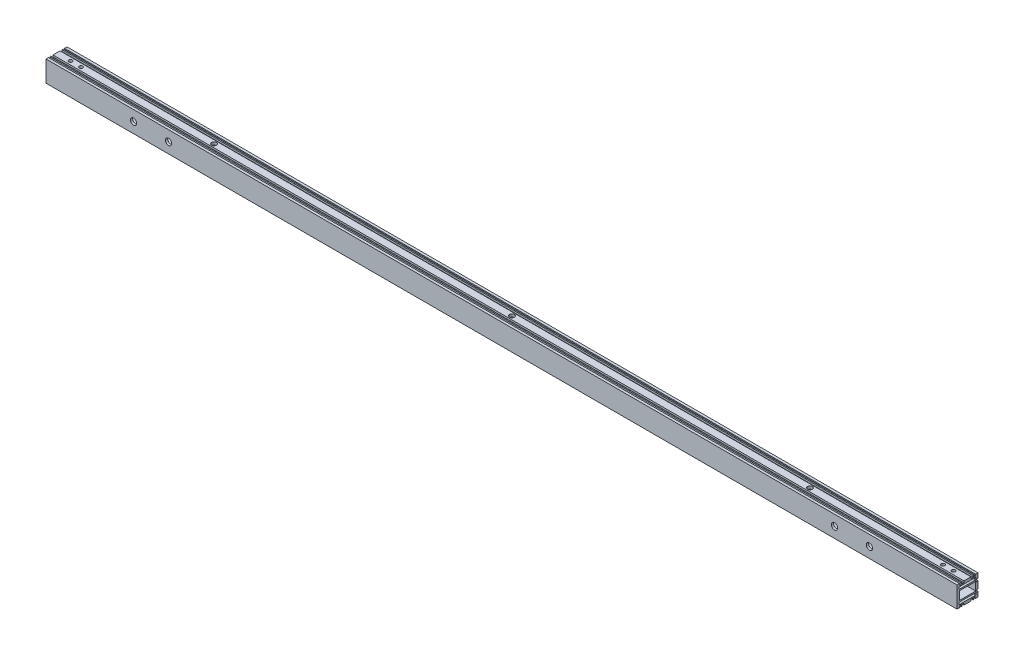
SolidWorks part; units mm, degrees
ref_plane "前视基准面" through (0, 0, 0) normal (0, 0, 1) x (1, 0, 0)
ref_plane "上视基准面" through (0, 0, 0) normal (0, 1, 0) x (1, 0, 0)
ref_plane "右视基准面" through (0, 0, 0) normal (1, 0, 0) x (0, 0, -1)
sketch "草图1" plane through (0, 0, 0) normal (1, 0, 0) x (0, 0, -1)
  line L0 (-15, 15) -> (15, -15) construction
  line L1 (-15, 15) -> (-11.5, 15)
  line L2 (-15, 15) -> (-15, -15)
  line L3 (-15, -15) -> (-11.5, -15)
  line L4 (15, 15) -> (15, 8)
  line L5 (15, 15) -> (-15, -15) construction
  line L6 (-11.5, 15) -> (-11.5, 13.5)
  line L7 (-11.5, 13.5) -> (-11, 13.5)
  line L8 (-11, 13.5) -> (-11, 12)
  line L9 (-11, 12) -> (-9.5, 12)
  line L10 (-9.5, 12) -> (-9.5, 15)
  line L11 (-9.5, 15) -> (-8, 15)
  line L12 (-8, 15) -> (-8, 12.5)
  line L13 (-8, 12.5) -> (-5, 12.5)
  line L14 (-5, 12.5) -> (-5, 15)
  line L15 (-5, 15) -> (5, 15)
  line L16 (0, 21.5201) -> (0, -18.309) construction
  line L17 (0, 55) -> (0, -55) construction
  line L18 (5, 12.5) -> (5, 15)
  line L19 (8, 12.5) -> (5, 12.5)
  line L20 (8, 15) -> (8, 12.5)
  line L21 (9.5, 15) -> (8, 15)
  line L22 (9.5, 12) -> (9.5, 15)
  line L23 (11, 12) -> (9.5, 12)
  line L24 (11, 13.5) -> (11, 12)
  line L25 (11.5, 13.5) -> (11, 13.5)
  line L26 (11.5, 15) -> (11.5, 13.5)
  line L27 (8, 15) -> (9.5, 15)
  line L28 (11.5, 15) -> (15, 15)
  line L29 (-19.8303, 0) -> (22.13, 0) construction
  line L30 (55, 0) -> (-55, 0) construction
  line L31 (8, -15) -> (9.5, -15)
  line L32 (11.5, -15) -> (11.5, -13.5)
  line L33 (11.5, -13.5) -> (11, -13.5)
  line L34 (11, -13.5) -> (11, -12)
  line L35 (11, -12) -> (9.5, -12)
  line L36 (9.5, -12) -> (9.5, -15)
  line L37 (9.5, -15) -> (8, -15)
  line L38 (8, -15) -> (8, -12.5)
  line L39 (8, -12.5) -> (5, -12.5)
  line L40 (5, -12.5) -> (5, -15)
  line L41 (-5, -15) -> (5, -15)
  line L42 (-5, -12.5) -> (-5, -15)
  line L43 (-8, -12.5) -> (-5, -12.5)
  line L44 (-8, -15) -> (-8, -12.5)
  line L45 (-9.5, -15) -> (-8, -15)
  line L46 (-9.5, -12) -> (-9.5, -15)
  line L47 (-11, -12) -> (-9.5, -12)
  line L48 (-11, -13.5) -> (-11, -12)
  line L49 (-11.5, -13.5) -> (-11, -13.5)
  line L50 (-11.5, -15) -> (-11.5, -13.5)
  line L51 (-9.5, -15) -> (-8, -15)
  line L52 (-5, -15) -> (5, -15)
  line L53 (8, -15) -> (9.5, -15)
  line L54 (11.5, -15) -> (15, -15)
  line L55 (15, 8) -> (12.5, 8)
  line L56 (12.5, 8) -> (12.5, 5)
  line L57 (12.5, 5) -> (15, 5)
  line L58 (12.5, -5) -> (15, -5)
  line L59 (12.5, -8) -> (12.5, -5)
  line L60 (15, -8) -> (12.5, -8)
  line L61 (15, 5) -> (15, -5)
  line L62 (15, -8) -> (15, -15)
  line L63 (12, -10.5) -> (12, -8.5)
  line L64 (-11.5, 11) -> (11.5, 11)
  line L65 (-12, 10.5) -> (-12, 8.5)
  line L66 (-11.5, 8) -> (11.5, 8)
  line L67 (12, 10.5) -> (12, 8.5)
  line L68 (-11.5, -8) -> (11.5, -8)
  line L69 (-12, -10.5) -> (-12, -8.5)
  line L70 (-11.5, -11) -> (11.5, -11)
  line L72 (-11.75, 6) -> (11.75, 6)
  line L73 (-11.75, 6) -> (-11.75, -6)
  line L74 (-11.75, -6) -> (11.75, -6)
  line L75 (11.75, 6) -> (11.75, -6)
  arc A0 (12, 8.5) -> (11.5, 8) centre (11.5, 8.5) cw
  arc A1 (11.5, 11) -> (12, 10.5) centre (11.5, 10.5) cw
  arc A2 (-11.5, 11) -> (-12, 10.5) centre (-11.5, 10.5) ccw
  arc A3 (-11.5, 8) -> (-12, 8.5) centre (-11.5, 8.5) cw
  arc A8 (-11.5, -8) -> (-12, -8.5) centre (-11.5, -8.5) ccw
  arc A9 (-11.5, -11) -> (-12, -10.5) centre (-11.5, -10.5) cw
  arc A10 (11.5, -11) -> (12, -10.5) centre (11.5, -10.5) ccw
  arc A11 (12, -8.5) -> (11.5, -8) centre (11.5, -8.5) ccw
  point P69 (12, 11)
  point P72 (-12, 11)
  point P77 (-11, -13.5)
  point P80 (11, -13.5)
  point P83 (11, 13.5)
  point P86 (-11, 13.5)
  point P99 (-12, -11)
  point P100 (12, -11)
  dimension "D17" = 0.5
  dimension "D1" = 3.5
  dimension "D2" = 1.5
  dimension "D3" = 0.5
  dimension "D4" = 1.5
  dimension "D5" = 3
  dimension "D6" = 30
  dimension "D7" = 30
  dimension "D8" = 1.5
  dimension "D9" = 2.5
  dimension "D10" = 3
  dimension "D11" = 2.5
  dimension "D12" = 7
  dimension "D13" = 3
  dimension "D14" = 4
  dimension "D15" = 3
  dimension "D16" = 24
  dimension "D19" = 23.5
  dimension "D20" = 12
extrude "凸台-拉伸1" add sketch "草图1" along normal mid plane 1301
hole_wizard "M6 螺纹孔1" positions "草图3" profile "草图2" tap size "M6" standard "GB"
sketch "草图3" plane through (0, 15, 0) normal (0, 1, 0) x (1, 0, 0)
  point P0 (630.5, 0)
  point P3 (615.5, 0)
  point P6 (-630.5, 0)
  point P9 (-615.5, 0)
sketch "草图2" plane through (630.5, 15, 0) normal (1, 0, 0) x (0, 0, 1)
  line L0 (0, 0) -> (0, 20.5022)
  line L1 (0, 20.5022) -> (2.5, 19)
  line L2 (2.5, 19) -> (2.5, 0)
  line L5 (2.5, 0) -> (0, 0)
  line L10 (0, 20.5022) -> (-2.5, 19) construction
  line L11 (0, -6.35) -> (0, 107.95) construction
  dimension "螺纹孔钻头直径" = 5
  dimension "螺纹孔钻头深度" = 19
  dimension "导头角度" = 118
cosmetic thread "孔螺蚊线1" parameters "D1"=9, "D2"=6
cosmetic thread "孔螺蚊线2" parameters "D1"=9, "D2"=6
cosmetic thread "孔螺蚊线3" parameters "D1"=9, "D2"=6
cosmetic thread "孔螺蚊线4" parameters "D1"=9, "D2"=6
hole_wizard "M6 螺纹孔2" positions "草图5" profile "草图4" tap size "M6" standard "GB"
sketch "草图5" plane through (0, 0, -15) normal (0, 0, -1) x (-1, 0, 0)
  point P0 (-630.5, 0)
  point P3 (-615.5, 0)
  point P6 (615.5, 0)
  point P9 (630.5, 0)
sketch "草图4" plane through (630.5, 0, -15) normal (1, 0, 0) x (0, 1, 0)
  line L0 (0, 0) -> (0, 20.5022)
  line L1 (0, 20.5022) -> (2.5, 19)
  line L2 (2.5, 19) -> (2.5, 0)
  line L5 (2.5, 0) -> (0, 0)
  line L10 (0, 20.5022) -> (-2.5, 19) construction
  line L11 (0, -6.35) -> (0, 107.95) construction
  dimension "螺纹孔钻头直径" = 5
  dimension "螺纹孔钻头深度" = 19
  dimension "导头角度" = 118
cosmetic thread "孔螺蚊线5" parameters "D1"=3.25, "D2"=6
cosmetic thread "孔螺蚊线6" parameters "D1"=3.25, "D2"=6
cosmetic thread "孔螺蚊线7" parameters "D1"=3.25, "D2"=6
cosmetic thread "孔螺蚊线8" parameters "D1"=3.25, "D2"=6
hole_wizard "Ø9.0 (9) 直径孔1" positions "草图7" profile "草图8" hole size "Ø9.0" standard "GB" end condition through all
sketch "草图7" plane through (0, 0, 15) normal (0, 0, 1) x (1, 0, 0)
  line L0 (650.5, -15) -> (-650.5, -15) construction
  line L1 (650.5, 15) -> (650.5, -15) construction
  line L2 (650.5, -15) -> (-650.5, -15) construction
  line L3 (-650.5, 15) -> (-650.5, -15) construction
  point P0 (-525.5, 0)
  point P2 (-475.5, 0)
  point P4 (525.5, 0)
  point P6 (475.5, 0)
  dimension "D1" = 15
  dimension "D2" = 125
  dimension "D3" = 15
  dimension "D4" = 175
  dimension "D5" = 15
  dimension "D6" = 125
  dimension "D7" = 15
  dimension "D8" = 175
sketch "草图8" plane through (-525.5, 0, 15) normal (1, 0, 0) x (0, -1, 0)
  line L0 (0, 0) -> (0, 30)
  line L1 (0, 30) -> (4.5, 30)
  line L2 (4.5, 30) -> (4.5, 0)
  line L5 (4.5, 0) -> (0, 0)
  line L11 (0, -6.35) -> (0, 107.95) construction
  dimension "通孔孔直径" = 9
  dimension "通孔孔深度" = 30
hole_wizard "M6 螺纹孔3" positions "草图10" profile "草图11" tap size "M6" standard "GB"
sketch "草图10" plane through (0, -15, 0) normal (0, -1, 0) x (-1, 0, 0)
  line L0 (-650.5, -15) -> (650.5, -15) construction
  line L1 (650.5, -5) -> (650.5, 5) construction
  line L3 (-650.5, -5) -> (-650.5, 5) construction
  point P0 (425.5, 0)
  point P2 (0, 0)
  point P4 (-425.5, 0)
  dimension "D1" = 15
  dimension "D2" = 225
  dimension "D3" = 650.5
  dimension "D4" = 15
  dimension "D5" = 15
  dimension "D6" = 225
sketch "草图11" plane through (-425.5, -15, 0) normal (1, 0, 0) x (0, 0, -1)
  line L0 (0, 0) -> (0, 16.5022)
  line L1 (0, 16.5022) -> (2.5, 15)
  line L2 (2.5, 15) -> (2.5, 0)
  line L5 (2.5, 0) -> (0, 0)
  line L10 (0, 16.5022) -> (-2.5, 15) construction
  line L11 (0, -6.35) -> (0, 107.95) construction
  dimension "螺纹孔钻头直径" = 5
  dimension "螺纹孔钻头深度" = 15
  dimension "导头角度" = 118
cosmetic thread "孔螺蚊线9" parameters "D1"=9, "D2"=6
cosmetic thread "孔螺蚊线10" parameters "D1"=9, "D2"=6
cosmetic thread "孔螺蚊线11" parameters "D1"=9, "D2"=6
hole_wizard "Ø7.0 (7) 直径孔1" positions "草图13" profile "草图12" hole size "Ø7.0" standard "GB"
sketch "草图13" plane through (0, 15, 0) normal (0, 1, 0) x (1, 0, 0)
  line L0 (650.5, 15) -> (-650.5, 15) construction
  line L1 (-650.5, -5) -> (-650.5, 5) construction
  line L2 (650.5, 15) -> (-650.5, 15) construction
  line L3 (650.5, 11.5) -> (650.5, 15) construction
  point P0 (425.5, 0)
  point P2 (0, 0)
  point P4 (-425.5, 0)
  dimension "D1" = 15
  dimension "D2" = 225
  dimension "D3" = 650.5
  dimension "D4" = 15
  dimension "D5" = 225
  dimension "D6" = 15
sketch "草图12" plane through (425.5, 15, 0) normal (1, 0, 0) x (0, 0, 1)
  line L0 (0, 0) -> (0, 17.103)
  line L1 (0, 17.103) -> (3.5, 15)
  line L2 (3.5, 15) -> (3.5, 0)
  line L5 (3.5, 0) -> (0, 0)
  line L10 (0, 17.103) -> (-3.5, 15) construction
  line L11 (0, -6.35) -> (0, 107.95) construction
  dimension "孔直径" = 7
  dimension "孔深度" = 15
  dimension "导头角度" = 118
